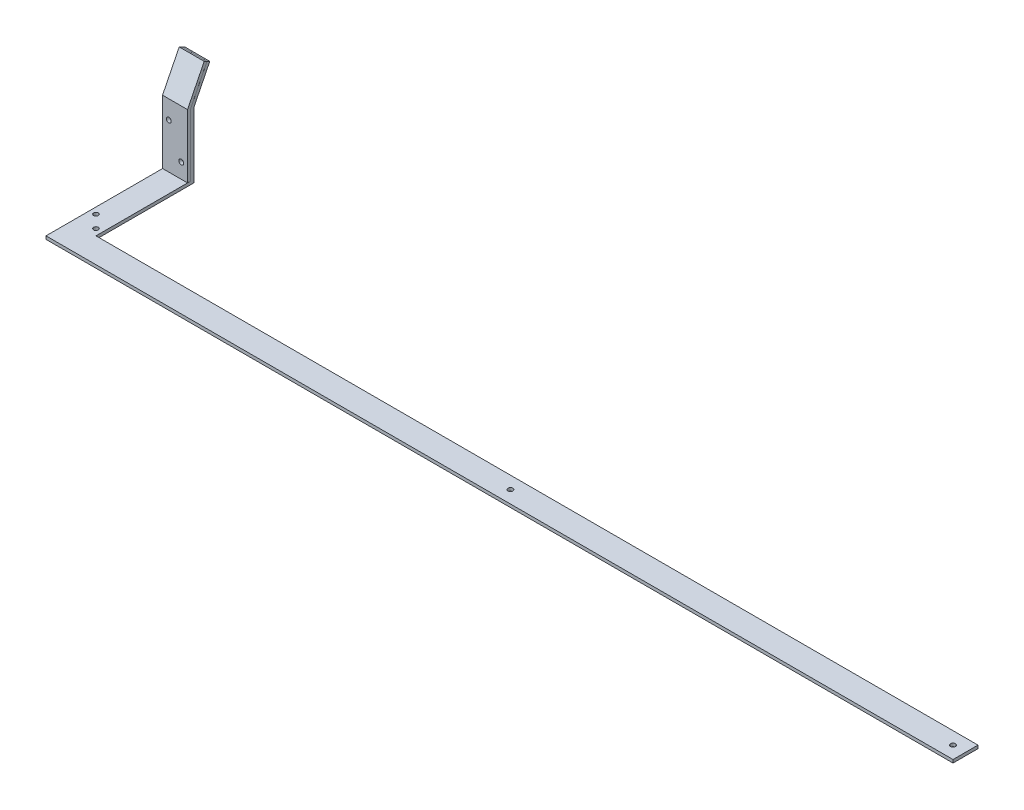
SolidWorks part; units mm, degrees
ref_plane "Alzado" through (0, 0, 0) normal (0, 0, 1) x (1, 0, 0)
ref_plane "Planta" through (0, 0, 0) normal (0, 1, 0) x (1, 0, 0)
ref_plane "Vista lateral" through (0, 0, 0) normal (1, 0, 0) x (0, 0, -1)
sketch "Croquis1" plane through (0, 0, 0) normal (0, 1, 0) x (1, 0, 0)
  line L0 (1742.85, -198.9028) -> (1742.85, -249.7028)
  line L1 (1742.85, -249.7028) -> (-50.8, -249.7028)
  line L2 (-50.8, -249.7028) -> (-50.8, 0)
  line L3 (-50.8, 0) -> (0, 0)
  line L4 (0, 0) -> (0, -198.9028)
  line L5 (0, -198.9028) -> (1742.85, -198.9028)
  dimension "D1" = 1793.65
  dimension "D2" = 50.8
  dimension "D3" = 1742.85
  dimension "D4" = 249.7028
extrude "Saliente-Extruir1" add sketch "Croquis1" along normal blind 6.31
sketch "Croquis2" plane through (-50.8, 0, 0) normal (-1, 0, 0) x (0, 0, 1)
  line L0 (0, 6.31) -> (0, 132.55)
  line L1 (0, 132.55) -> (-32.5724, 197.8802)
  line L2 (6.31, 6.31) -> (6.31, 134.0358)
  line L3 (6.31, 134.0358) -> (-26.9254, 200.6957)
  line L4 (-32.5724, 197.8802) -> (-26.9254, 200.6957)
  line L5 (0, 6.31) -> (6.31, 6.31)
  dimension "D1" = 153.5
  dimension "D2" = 126.24
  dimension "D3" = 73
  dimension "D4" = 6.31
extrude "Saliente-Extruir2" add sketch "Croquis2" against normal blind 50.8
sketch "Croquis3" plane through (-50.8, 0, 0) normal (-1, 0, 0) x (0, 0, 1)
  line L0 (6.31, 6.31) -> (6.31, 134.0358) construction
  line L1 (6.31, 134.0358) -> (-26.9254, 200.6957) construction
  line L2 (6.41, 6.41) -> (6.41, 134.0594)
  line L3 (6.41, 134.0594) -> (-26.8359, 200.7403)
  line L4 (12.72, 6.41) -> (12.72, 135.5452)
  line L5 (12.72, 135.5452) -> (-21.1889, 203.5558)
  line L6 (-26.8359, 200.7403) -> (-21.1889, 203.5558)
  line L7 (6.41, 6.41) -> (12.72, 6.41)
  line L8 (6.31, 6.31) -> (249.7028, 6.31) construction
  line L10 (6.41, 6.31) -> (6.41, 134.0594) construction
  line L11 (12.72, 6.31) -> (12.72, 135.5452) construction
  dimension "D3" = 0.1
  dimension "D1" = 0.1
  dimension "D2" = 6.31
extrude "Saliente-Extruir3" add sketch "Croquis3" against normal blind 50.8 separate body
sketch "Croquis4" plane through (1742.85, 0, 0) normal (1, 0, 0) x (0, 0, -1)
  line L0 (-249.7028, 6.31) -> (-198.9028, 6.31)
  line L1 (-198.9028, 6.31) -> (-198.9028, 0)
  line L2 (-198.9028, 0) -> (-249.7028, 0)
  line L3 (-249.7028, 0) -> (-249.7028, 6.31)
extrude "Saliente-Extruir4" add sketch "Croquis4" along normal blind 50.8
sketch "Croquis5" plane through (0, 0, 0) normal (0, -1, 0) x (-1, 0, 0)
  circle A0 centre (38.1, -160.8028) radius 4.7625
  circle A1 centre (12.7, -186.2028) radius 4.7625
extrude "Cortar-Extruir1" cut sketch "Croquis5" against normal blind 50
sketch "Croquis6" plane through (0, 0, 0) normal (0, -1, 0) x (-1, 0, 0)
  line L0 (-862.0698, -229.3826) -> (-868.25, -224.3028) construction
  line L1 (-868.25, -224.3028) -> (-868.25, -216.3028) construction
  circle A0 centre (-868.25, -224.3028) radius 8 construction
  circle A1 centre (-868.25, -224.3028) radius 5
extrude "Cortar-Extruir2" cut sketch "Croquis6" against normal blind 50
sketch "Croquis7" plane through (0, 0, 0) normal (0, -1, 0) x (-1, 0, 0)
  line L0 (-1768.25, -229.0653) -> (-1768.25, -224.3028) construction
  line L1 (-1768.25, -224.3028) -> (-1763.4875, -224.3028) construction
  circle A0 centre (-1768.25, -224.3028) radius 4.7625 construction
  circle A1 centre (-1768.25, -224.3028) radius 5
  dimension "D1" = 10
extrude "Cortar-Extruir3" cut sketch "Croquis7" against normal blind 50
sketch "Croquis8" plane through (0, 0, 12.72) normal (0, 0, 1) x (1, 0, 0)
  line L0 (-25.4, 6.31) -> (-25.4, 135.5452) construction
  line L1 (0, 6.31) -> (-50.8, 6.31) construction
  line L2 (0, 135.5452) -> (-50.8, 135.5452) construction
  line L3 (-25.4, 6.31) -> (0, 6.31) construction
  line L4 (0, 6.31) -> (-12.7, 6.31) construction
  line L5 (-12.7, 6.31) -> (-12.7, 36.91) construction
  line L6 (-12.7, 36.91) -> (-50.8, 36.91) construction
  line L7 (-50.8, 6.41) -> (-50.8, 135.5452) construction
  line L8 (-50.8, 36.91) -> (-25.4, 36.91) construction
  line L9 (-25.4, 36.91) -> (-38.1, 36.91) construction
  line L10 (-38.1, 36.91) -> (-38.1, 98.1) construction
  circle A0 centre (-38.1, 98.1) radius 5
  circle A1 centre (-12.7, 36.91) radius 5
  dimension "D3" = 10
  dimension "D4" = 10
  dimension "D1" = 30.6
  dimension "D2" = 61.19
extrude "Cortar-Extruir4" cut sketch "Croquis8" against normal blind 24
